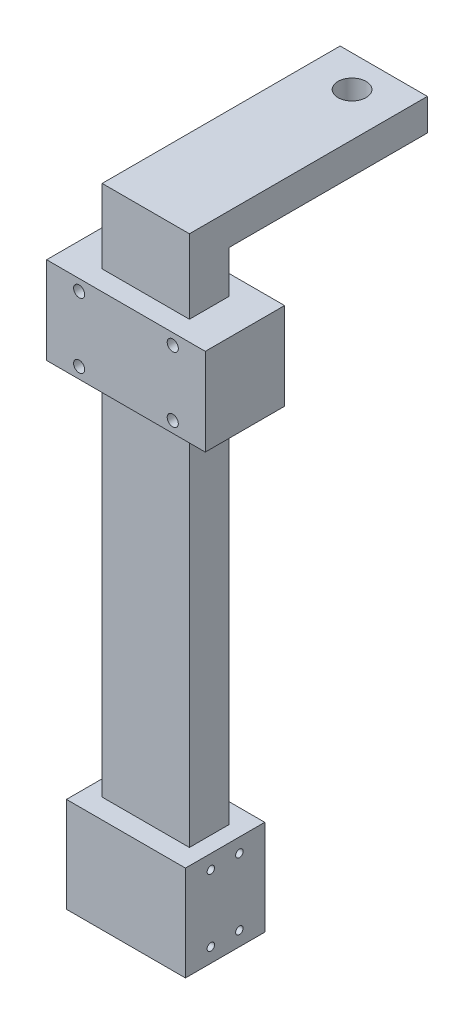
SolidWorks part; units mm, degrees
ref_plane "Front Plane" through (0, 0, 0) normal (0, 0, 1) x (1, 0, 0)
ref_plane "Top Plane" through (0, 0, 0) normal (0, 1, 0) x (1, 0, 0)
ref_plane "Right Plane" through (0, 0, 0) normal (1, 0, 0) x (0, 0, -1)
sketch "Sketch1" plane through (0, 0, 0) normal (0, 1, 0) x (1, 0, 0)
  line L1 (-6.985, -3.175) -> (6.985, -3.175)
  line L2 (-6.985, -3.175) -> (-6.985, 3.175)
  line L3 (-6.985, 3.175) -> (6.985, 3.175)
  line L4 (6.985, -3.175) -> (6.985, 3.175)
  line L5 (-6.985, -3.175) -> (6.985, 3.175) construction
  line L6 (-6.985, 3.175) -> (6.985, -3.175) construction
  point P0 (0, 0)
  dimension "D1" = 13.97
  dimension "D2" = 6.35
extrude "Boss-Extrude1" add sketch "Sketch1" along normal blind 95.25
sketch "Sketch3" plane through (0, 0, 3.175) normal (0, 0, 1) x (1, 0, 0)
  line L0 (0, 0) -> (0, 95.25) construction
  line L1 (-6.985, 95.25) -> (6.985, 95.25) construction
  line L3 (-12.7, 74.5062) -> (12.7, 74.5062)
  line L4 (-12.7, 74.5062) -> (-12.7, 88.4762)
  line L5 (-12.7, 88.4762) -> (12.7, 88.4762)
  line L6 (12.7, 74.5062) -> (12.7, 88.4762)
  line L7 (-12.7, 74.5062) -> (12.7, 88.4762) construction
  line L8 (-12.7, 88.4762) -> (12.7, 74.5062) construction
  point P5 (0, 81.4912)
  dimension "D1" = 13.97
  dimension "D2" = 25.4
extrude "Boss-Extrude3" add sketch "Sketch3" against normal blind 6.35
sketch "Sketch5" plane through (0, 0, 0) normal (1, 0, 0) x (0, 0, -1)
  line L0 (0, 0) -> (0, 74.5062) construction
  line L1 (3.175, 74.5062) -> (-3.175, 74.5062) construction
  line L2 (-3.175, 0) -> (3.175, 0) construction
  line L3 (-6.35, 0) -> (6.35, 0)
  line L4 (-6.35, 0) -> (-6.35, 15.24)
  line L5 (-6.35, 15.24) -> (6.35, 15.24)
  line L6 (6.35, 0) -> (6.35, 15.24)
  line L7 (-6.35, 0) -> (6.35, 15.24) construction
  line L8 (-6.35, 15.24) -> (6.35, 0) construction
  point P5 (0, 7.62)
  dimension "D1" = 12.7
  dimension "D2" = 15.24
extrude "Boss-Extrude5" add sketch "Sketch5" along normal blind 9.525 and the other way blind 9.525
sketch "Sketch6" plane through (0, 95.25, 0) normal (0, 1, 0) x (1, 0, 0)
  line L0 (6.985, -3.175) -> (6.985, 3.175) construction
  line L1 (-6.985, -3.175) -> (6.985, -3.175)
  line L2 (-6.985, -3.175) -> (-6.985, 34.925)
  line L3 (-6.985, 34.925) -> (6.985, 34.925)
  line L4 (6.985, -3.175) -> (6.985, 34.925)
  dimension "D1" = 38.1
extrude "Boss-Extrude6" add sketch "Sketch6" along normal blind 5.08
sketch "Sketch7" plane through (0, 100.33, 0) normal (0, 1, 0) x (1, 0, 0)
  line L0 (0, -3.175) -> (0, 34.925) construction
  line L1 (-6.985, -3.175) -> (6.985, -3.175) construction
  line L2 (6.985, 34.925) -> (-6.985, 34.925) construction
  circle A0 centre (0, 29.845) radius 2.25
  dimension "D1" = 4.5
  dimension "D2" = 5.08
extrude "Cut-Extrude1" cut sketch "Sketch7" against normal blind 5.08
sketch "Sketch8" plane through (-9.525, 0, 0) normal (-1, 0, 0) x (0, 0, 1)
  line L0 (0, 0) -> (0, 15.24) construction
  line L1 (-3.175, 15.24) -> (3.175, 15.24) construction
  line L2 (-6.35, 7.62) -> (6.35, 7.62) construction
  line L3 (-6.35, 0) -> (-6.35, 15.24) construction
  line L4 (6.35, 15.24) -> (6.35, 0) construction
  line L6 (-2.286, 2.286) -> (2.286, 2.286) construction
  line L7 (-2.286, 2.286) -> (-2.286, 12.954) construction
  line L8 (-2.286, 12.954) -> (2.286, 12.954) construction
  line L9 (2.286, 2.286) -> (2.286, 12.954) construction
  line L10 (-2.286, 2.286) -> (2.286, 12.954) construction
  line L11 (-2.286, 12.954) -> (2.286, 2.286) construction
  circle A0 centre (-2.286, 12.954) radius 0.5956
  circle A1 centre (2.286, 12.954) radius 0.5956
  circle A2 centre (2.286, 2.286) radius 0.5956
  circle A3 centre (-2.286, 2.286) radius 0.5956
  point P11 (0, 7.62)
  dimension "D3" = 1.1913
  dimension "D4" = 1.1913
  dimension "D5" = 1.1913
  dimension "D6" = 1.1913
  dimension "D1" = 5.334
  dimension "D2" = 2.286
extrude "Cut-Extrude2" cut sketch "Sketch8" against normal through all
sketch "Sketch9" plane through (0, 0, 3.175) normal (0, 0, 1) x (1, 0, 0)
  line L0 (-12.7, 81.4912) -> (12.7, 81.4912) construction
  line L1 (-12.7, 88.4762) -> (-12.7, 74.5062) construction
  line L2 (12.7, 74.5062) -> (12.7, 88.4762) construction
  line L3 (0, 100.33) -> (0, 0) construction
  line L4 (-6.985, 100.33) -> (6.985, 100.33) construction
  line L6 (-7.493, 76.2842) -> (7.493, 76.2842) construction
  line L7 (-7.493, 76.2842) -> (-7.493, 86.6982) construction
  line L8 (-7.493, 86.6982) -> (7.493, 86.6982) construction
  line L9 (7.493, 76.2842) -> (7.493, 86.6982) construction
  line L10 (-7.493, 76.2842) -> (7.493, 86.6982) construction
  line L11 (-7.493, 86.6982) -> (7.493, 76.2842) construction
  circle A0 centre (-7.493, 86.6982) radius 0.889
  circle A1 centre (7.493, 86.6982) radius 0.889
  circle A2 centre (7.493, 76.2842) radius 0.889
  circle A3 centre (-7.493, 76.2842) radius 0.889
  point P11 (0, 81.4912)
  dimension "D3" = 1.778
  dimension "D4" = 1.778
  dimension "D5" = 1.778
  dimension "D6" = 1.778
  dimension "D1" = 14.986
  dimension "D2" = 10.414
extrude "Cut-Extrude3" cut sketch "Sketch9" against normal through all
sketch "Sketch10" plane through (0, 0, 0) normal (0, 0, 1) x (1, 0, 0)
  line L1 (-12.7, 74.5062) -> (12.7, 74.5062)
  line L2 (-12.7, 74.5062) -> (-12.7, 88.4762)
  line L3 (-12.7, 88.4762) -> (12.7, 88.4762)
  line L4 (12.7, 74.5062) -> (12.7, 88.4762)
  circle A0 centre (7.493, 86.6982) radius 0.889
  circle A1 centre (7.493, 76.2842) radius 0.889
  circle A2 centre (-7.493, 76.2842) radius 0.889
  circle A3 centre (-7.493, 86.6982) radius 0.889
extrude "Boss-Extrude7" add sketch "Sketch10" along normal blind 6.35 and the other way blind 6.35 contours L1 L4 L3 L2 A3 A2 A1 A0
